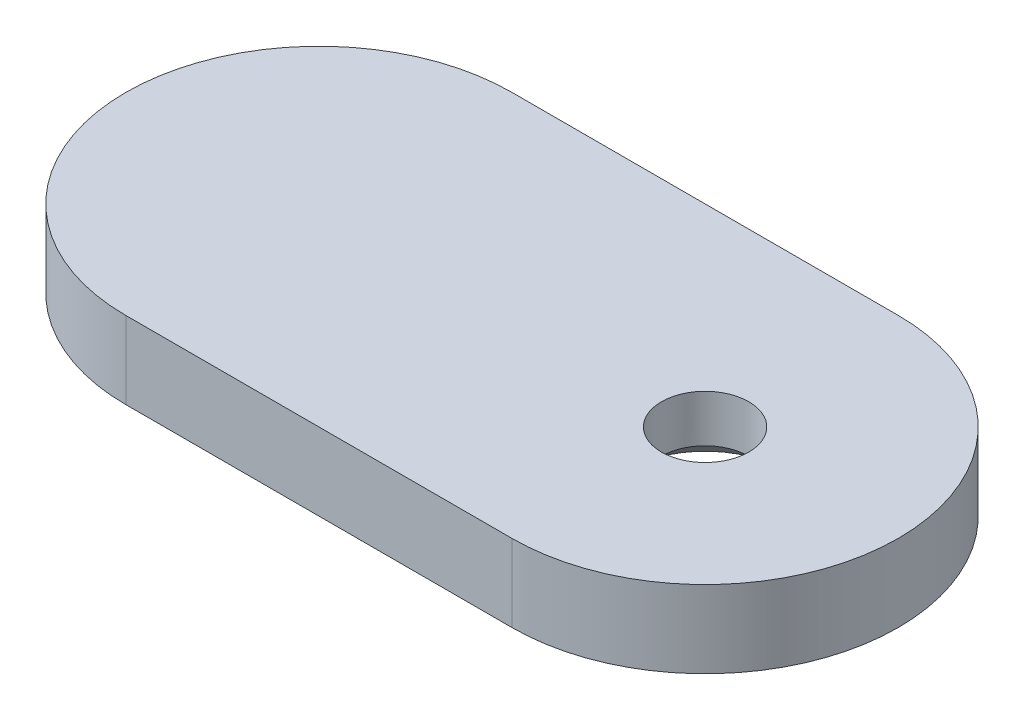
SolidWorks part; units mm, degrees
ref_plane "Front Plane" through (0, 0, 0) normal (0, 0, 1) x (1, 0, 0)
ref_plane "Top Plane" through (0, 0, 0) normal (0, 1, 0) x (1, 0, 0)
ref_plane "Right Plane" through (0, 0, 0) normal (1, 0, 0) x (0, 0, -1)
sketch "Sketch1" plane through (0, 0, 0) normal (0, 1, 0) x (1, 0, 0)
  line L0 (-6.9208, 0) -> (3.0792, 0) construction
  line L1 (-6.9208, 5) -> (3.0792, 5)
  line L2 (-6.9208, -5) -> (3.0792, -5)
  arc A0 (-6.9208, 5) -> (-6.9208, -5) centre (-6.9208, 0) ccw
  arc A1 (3.0792, -5) -> (3.0792, 5) centre (3.0792, 0) ccw
  point P2 (-1.9208, 0)
  dimension "D1" = 5
  dimension "D2" = 10
extrude "Boss-Extrude1" add sketch "Sketch1" along normal blind 2
hole_wizard "#4-40 Tapped Hole1" positions "Sketch2" profile "Sketch3" tap size "#4-40" standard "ANSI Inch"
sketch "Sketch2" plane through (28.7935, 0, 54.3529) normal (0, -1, 0) x (-0.6824, 0, -0.7309)
  point P0 (57.2771, 18.2976)
sketch "Sketch3" plane through (3.0792, 0, 0) normal (1, 0, 0) x (0, 0, -1)
  line L0 (0, 0) -> (0, 30.6792)
  line L1 (0, 30.6792) -> (1.1303, 30)
  line L2 (1.1303, 30) -> (1.1303, 0.7779)
  line L3 (1.1303, 0.7779) -> (2.0574, 0)
  line L4 (2.0574, 0) -> (0, 0)
  line L5 (-1.1303, 0.7779) -> (-2.0574, 0) construction
  line L6 (0, 30.6792) -> (-1.1303, 30) construction
  line L7 (0, -6.35) -> (0, 107.95) construction
  dimension "Tap Drill Dia." = 2.2606
  dimension "Tap Drill Depth" = 30
  dimension "Near C'Sink Dia." = 4.1148
  dimension "Near C'Sink Angle" = 100
  dimension "Drill Angle" = 118
cosmetic thread "Hole Thread1" parameters "D1"=2, "D2"=2.8448
